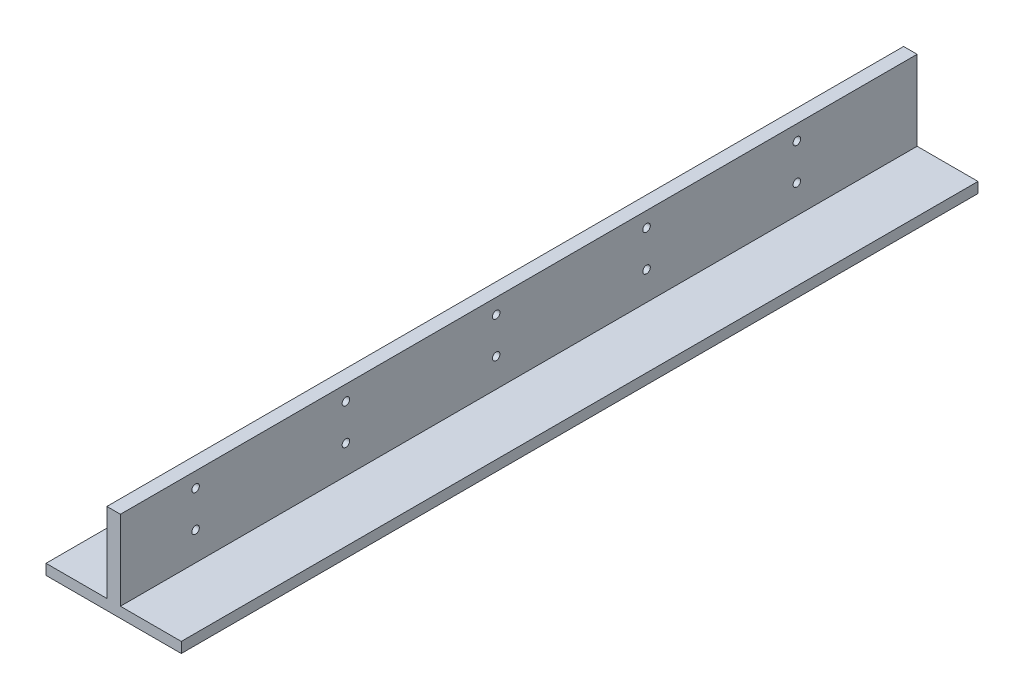
SolidWorks part; units mm, degrees
ref_plane "Plan de face" through (0, 0, 0) normal (0, 0, 1) x (1, 0, 0)
ref_plane "Plan de dessus" through (0, 0, 0) normal (0, 1, 0) x (1, 0, 0)
ref_plane "Plan de droite" through (0, 0, 0) normal (1, 0, 0) x (0, 0, -1)
sketch "Esquisse1" plane through (0, 0, 0) normal (0, 0, 1) x (1, 0, 0)
  line L0 (0, 0) -> (90, 0)
  line L1 (90, 0) -> (90, 7)
  line L2 (90, 7) -> (49.5, 7)
  line L3 (49.5, 7) -> (49.5, 60)
  line L4 (49.5, 60) -> (40.5, 60)
  line L5 (40.5, 60) -> (40.5, 7)
  line L6 (40.5, 7) -> (0, 7)
  line L7 (0, 7) -> (0, 0)
  dimension "D1" = 7
  dimension "D2" = 9
  dimension "D3" = 90
  dimension "D4" = 60
extrude "Boss.-Extru.1" add sketch "Esquisse1" along normal blind 530
sketch "Esquisse2" plane through (40.5, 0, 0) normal (-1, 0, 0) x (0, 0, 1)
  line L0 (0, 38) -> (530, 38) construction
  line L1 (0, 60) -> (0, 7) construction
  line L2 (530, 60) -> (530, 7) construction
  line L3 (530, 60) -> (0, 60) construction
  line L4 (80, 50) -> (180, 50) construction
  circle A0 centre (80, 50) radius 2.5
  circle A1 centre (80, 26) radius 2.5
  circle A2 centre (180, 50) radius 2.5
  circle A3 centre (180, 26) radius 2.5
  circle A4 centre (280, 50) radius 2.5
  circle A5 centre (280, 26) radius 2.5
  circle A6 centre (380, 50) radius 2.5
  circle A7 centre (380, 26) radius 2.5
  circle A8 centre (480, 50) radius 2.5
  circle A9 centre (480, 26) radius 2.5
  dimension "D2" = 12
  dimension "D4" = 5
  dimension "D1" = 22
  dimension "D3" = 80
  dimension "D6" = 100
  dimension "D5" = 5
extrude "Enlèv. mat.-Extru.1" cut sketch "Esquisse2" against normal up to vertex (9 mm away) up to point (49.5, 60, 0)
